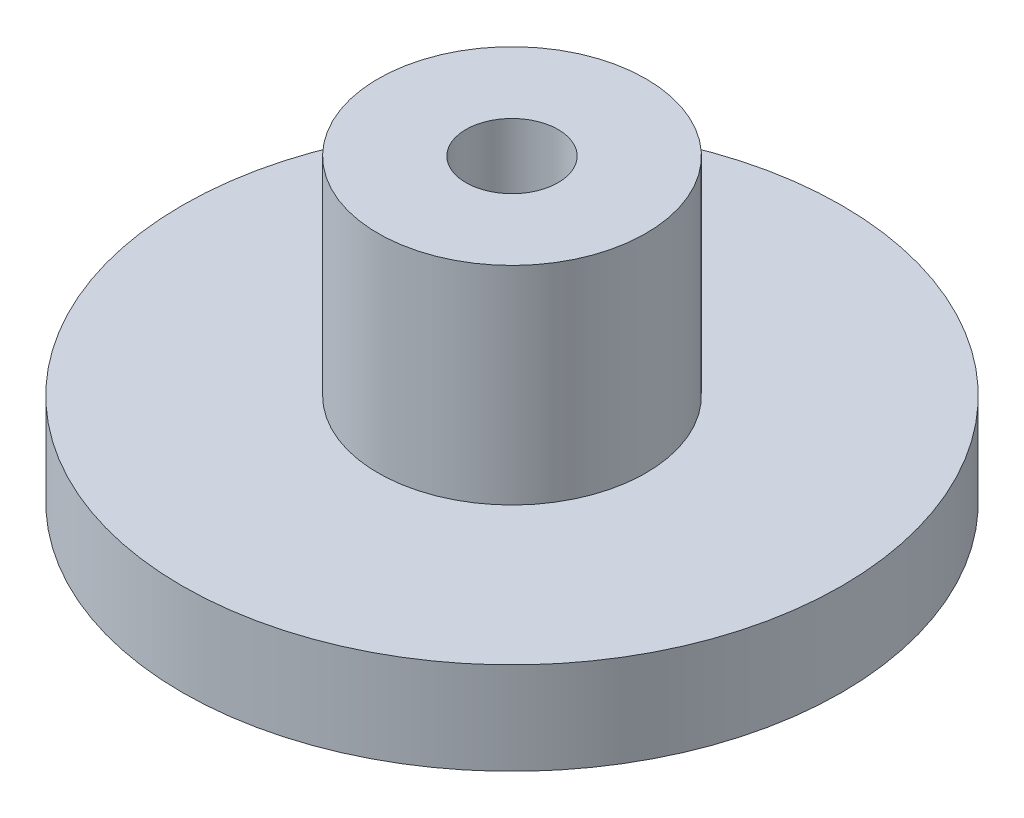
SolidWorks part; units mm, degrees
material "Nylon 101"
ref_plane "Front Plane" through (0, 0, 0) normal (0, 0, 1) x (1, 0, 0)
ref_plane "Top Plane" through (0, 0, 0) normal (0, 1, 0) x (1, 0, 0)
ref_plane "Right Plane" through (0, 0, 0) normal (1, 0, 0) x (0, 0, -1)
sketch "Sketch1" plane through (0, 0, 0) normal (0, 0, 1) x (1, 0, 0)
  line L0 (0, 0) -> (0, 6.5) construction
  line L1 (1, 6.5) -> (1, 0)
  line L2 (1, 0) -> (2.5, 0)
  line L3 (2.5, 0) -> (2.5, 0.6)
  line L4 (2.5, 0.6) -> (5.5, 0.6)
  line L5 (5.5, 0.6) -> (5.5, 0)
  line L6 (5.5, 0) -> (7.1501, 0)
  line L7 (7.1501, 0) -> (7.1501, 2)
  line L8 (7.1501, 2) -> (2.9051, 2)
  line L11 (2.9051, 2) -> (2.9051, 6.5)
  line L12 (2.9051, 6.5) -> (1, 6.5)
  line L13 (0, 6.5) -> (1, 6.5) construction
  line L14 (0, 0) -> (1, 0) construction
  dimension "D1" = 2
  dimension "D2" = 5
  dimension "D3" = 11
  dimension "D4" = 14.3002
  dimension "D5" = 5.8102
  dimension "D6" = 0.6
  dimension "D8" = 2
  dimension "D9" = 6.5
revolve "14 and 35" add sketch "Sketch1" angle 360 about L0
